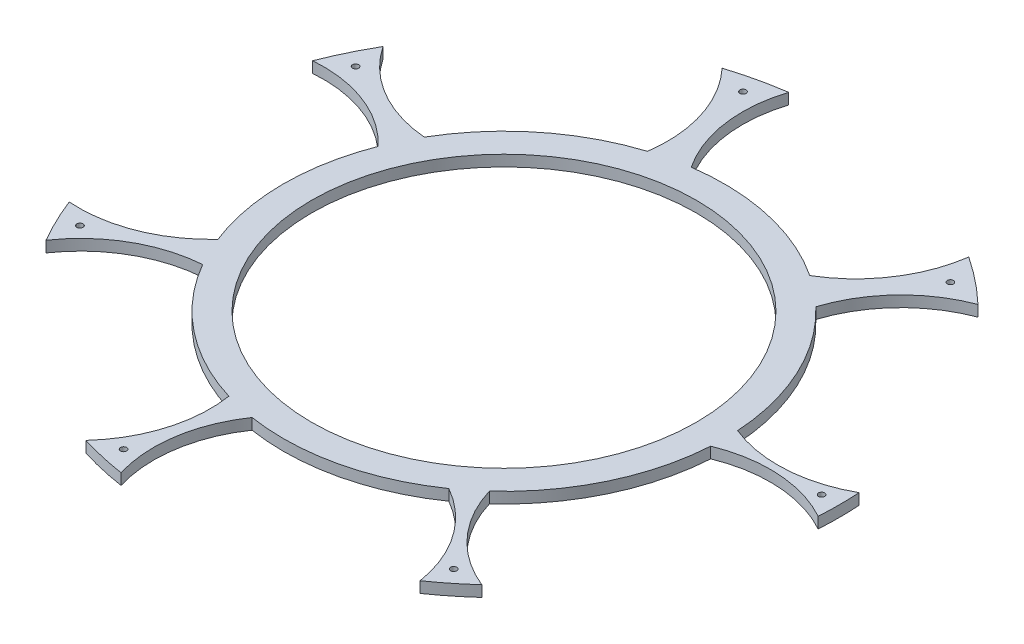
SolidWorks part; units mm, degrees
ref_plane "Front Plane" through (0, 0, 0) normal (0, 0, 1) x (1, 0, 0)
ref_plane "Top Plane" through (0, 0, 0) normal (0, 1, 0) x (1, 0, 0)
ref_plane "Right Plane" through (0, 0, 0) normal (1, 0, 0) x (0, 0, -1)
sketch "Sketch1" plane through (0, 0, 0) normal (0, 1, 0) x (1, 0, 0)
  circle A0 centre (0, 0) radius 63.5
  circle A1 centre (0, 0) radius 55.372
  dimension "D1" = 127
  dimension "D2" = 110.744
extrude "Boss-Extrude1" add sketch "Sketch1" along normal blind 3.175
sketch "Sketch2" plane through (0, 0, 0) normal (0, 1, 0) x (1, 0, 0)
  line L0 (0, 0) -> (143.528, 0) construction
  line L1 (0, 0) -> (63.3816, -3.8766) construction
  line L2 (0, 0) -> (89.4882, -112.2147) construction
  line L3 (0, 0) -> (-31.938, -139.9294) construction
  line L4 (0, 0) -> (-129.3142, -62.2744) construction
  line L5 (0, 0) -> (-129.3142, 62.2744) construction
  line L6 (0, 0) -> (-31.938, 139.9294) construction
  line L7 (0, 0) -> (89.4882, 112.2147) construction
  line L8 (0, 0) -> (143.528, 0) construction
  line L9 (0, 0) -> (89.4882, -112.2147) construction
  line L10 (0, 0) -> (100.2026, -110.0385) construction
  line L11 (0, 0) -> (-23.0943, -148.2025) construction
  line L12 (0, 0) -> (-133.3437, -76.8752) construction
  line L13 (0, 0) -> (-143.511, 55.7054) construction
  line L14 (0, 0) -> (-43.7126, 137.7399) construction
  line L15 (0, 0) -> (72.9258, 109.881) construction
  arc A0 (63.3816, -3.8766) -> (96.34, -5.8924) centre (77.7645, -39.1575) cw
  arc A1 (-13.6117, 95.5554) -> (-29.1962, 91.9983) centre (0, 0) ccw
  arc A2 (63.3816, 3.8766) -> (96.34, 5.8924) centre (77.7645, 39.1575) ccw
  circle A3 centre (0, 0) radius 63.5 construction
  arc A4 (96.34, -5.8924) -> (96.34, 5.8924) centre (0, 0) ccw
  arc A5 (63.3816, -3.8766) -> (63.3816, 3.8766) centre (0, 0) ccw
  arc A6 (42.7539, -46.9506) -> (64.9859, -71.3649) centre (79.2579, -36.039) ccw
  circle A7 centre (0, 0) radius 63.5 construction
  arc A9 (-8.9551, 62.8654) -> (-19.208, 60.5252) centre (0, 0) ccw
  arc A10 (-9.7772, -62.7428) -> (-14.8613, -95.369) centre (21.6083, -84.3428) ccw
  arc A11 (-55.0124, -31.7157) -> (-83.6188, -48.2079) centre (-52.1657, -69.7092) ccw
  arc A12 (-59.1968, 22.9779) -> (-89.9792, 34.9264) centre (-87.0131, -3.0579) ccw
  arc A13 (-29.1962, 91.9983) -> (-19.208, 60.5252) centre (-56.9305, 65.8752) cw
  arc A14 (35.114, 52.908) -> (53.3733, 80.4202) centre (15.6341, 85.6516) ccw
  arc A15 (36.2598, -52.1294) -> (55.1149, -79.2367) centre (17.4989, -85.2902) cw
  arc A16 (-18.4141, -60.7715) -> (-27.9895, -92.3726) centre (-56.0634, -66.6148) cw
  arc A17 (-59.096, -23.236) -> (-89.8259, -35.3187) centre (-87.0256, 2.6782) cw
  arc A18 (-54.8735, 31.9554) -> (-83.4077, 48.5723) centre (-51.861, 69.9362) cw
  arc A19 (-13.6117, 95.5554) -> (-8.9551, 62.8654) centre (22.7105, 84.0528) ccw
  arc A20 (43.7679, 46.0067) -> (66.5272, 69.9303) centre (80.0253, 34.3014) cw
  arc A21 (66.5272, 69.9303) -> (53.3733, 80.4202) centre (0, 0) ccw
  arc A22 (43.7679, 46.0067) -> (35.114, 52.908) centre (0, 0) ccw
  arc A23 (96.34, -5.8924) -> (96.34, 5.8924) centre (0, 0) ccw
  arc A24 (63.3816, -3.8766) -> (63.3816, 3.8766) centre (0, 0) ccw
  arc A25 (55.1149, -79.2367) -> (64.9859, -71.3649) centre (0, 0) ccw
  arc A26 (36.2598, -52.1294) -> (42.7539, -46.9506) centre (0, 0) ccw
  arc A27 (-18.4141, -60.7715) -> (-9.7772, -62.7428) centre (0, 0) ccw
  arc A28 (-27.9895, -92.3726) -> (-14.8613, -95.369) centre (0, 0) ccw
  arc A29 (-59.096, -23.236) -> (-55.0124, -31.7157) centre (0, 0) ccw
  arc A30 (-89.8259, -35.3187) -> (-83.6188, -48.2079) centre (0, 0) ccw
  arc A31 (-54.8735, 31.9554) -> (-59.1968, 22.9779) centre (0, 0) ccw
  arc A32 (-83.4077, 48.5723) -> (-89.9792, 34.9264) centre (0, 0) ccw
  point P84 (74.2802, 27.8883)
  circle M135 centre (0, 0) radius 63.5
  dimension "D1" = 38.1
  dimension "D2" = 193.04
  dimension "D3" = 7
  dimension "D5" = 51.429
  dimension "D6" = 3.75
  dimension "D7" = 4
  dimension "D8" = 4.25
  dimension "D12" = 38.1
  dimension "D4" = 3.5
  dimension "D9" = 4.5
  dimension "D10" = 4.75
  dimension "D11" = 5
extrude "Boss-Extrude2" add sketch "Sketch2" along normal blind 3.175 contours A4 A0 A2 M135 | A25 A15 A6 M135 | A28 A16 A10 M135 | A30 A17 A11 M135 | A32 A18 A12 M135 | A1 A19 A13 M135 | A21 A20 A14 M135
sketch "Sketch37" plane through (0, 3.175, 0) normal (0, 1, 0) x (1, 0, 0)
  line L0 (91.44, 0) -> (0, 0) construction
  circle A0 centre (91.44, 0) radius 0.889
  dimension "D1" = 1.778
  dimension "D2" = 91.44
extrude "Cut-Extrude19" cut sketch "Sketch37" against normal through all
pattern_circular "CirPattern7" count 7 over 360 about axis through (0, 0, 0) along (0, 1, 0) of "Cut-Extrude19"
